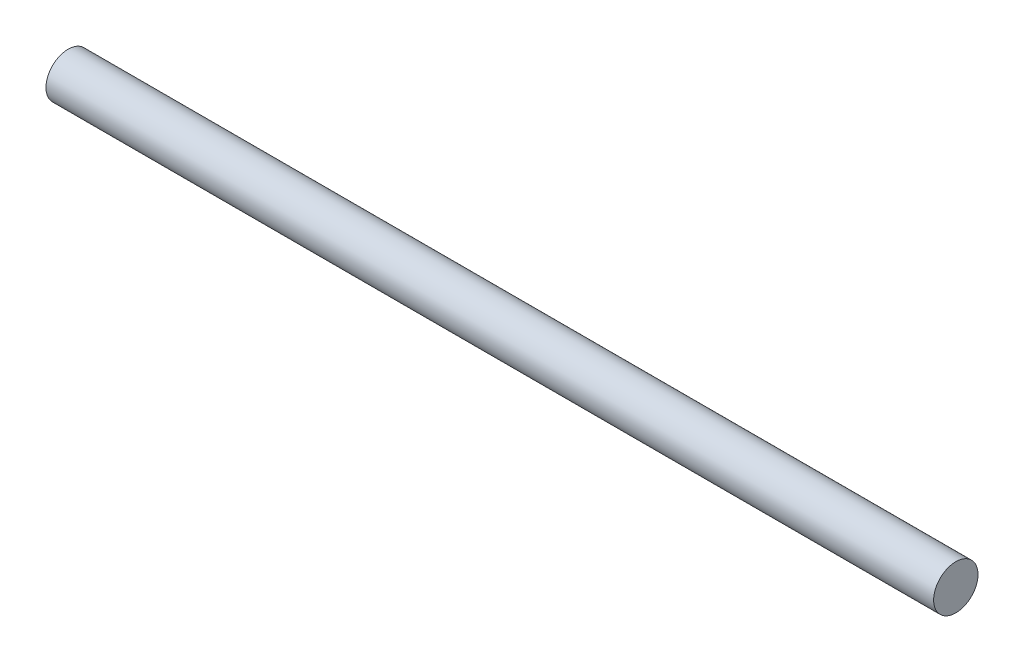
SolidWorks part; units mm, degrees
ref_plane "前基準面" through (0, 0, 0) normal (0, 0, 1) x (1, 0, 0)
ref_plane "上基準面" through (0, 0, 0) normal (0, 1, 0) x (1, 0, 0)
ref_plane "右基準面" through (0, 0, 0) normal (1, 0, 0) x (0, 0, -1)
sketch "草圖1" plane through (0, 0, 0) normal (1, 0, 0) x (0, 0, -1)
  circle A0 centre (0, 0) radius 2.5
  dimension "D1" = 5
extrude "填料-伸長1" add sketch "草圖1" along normal blind 100
